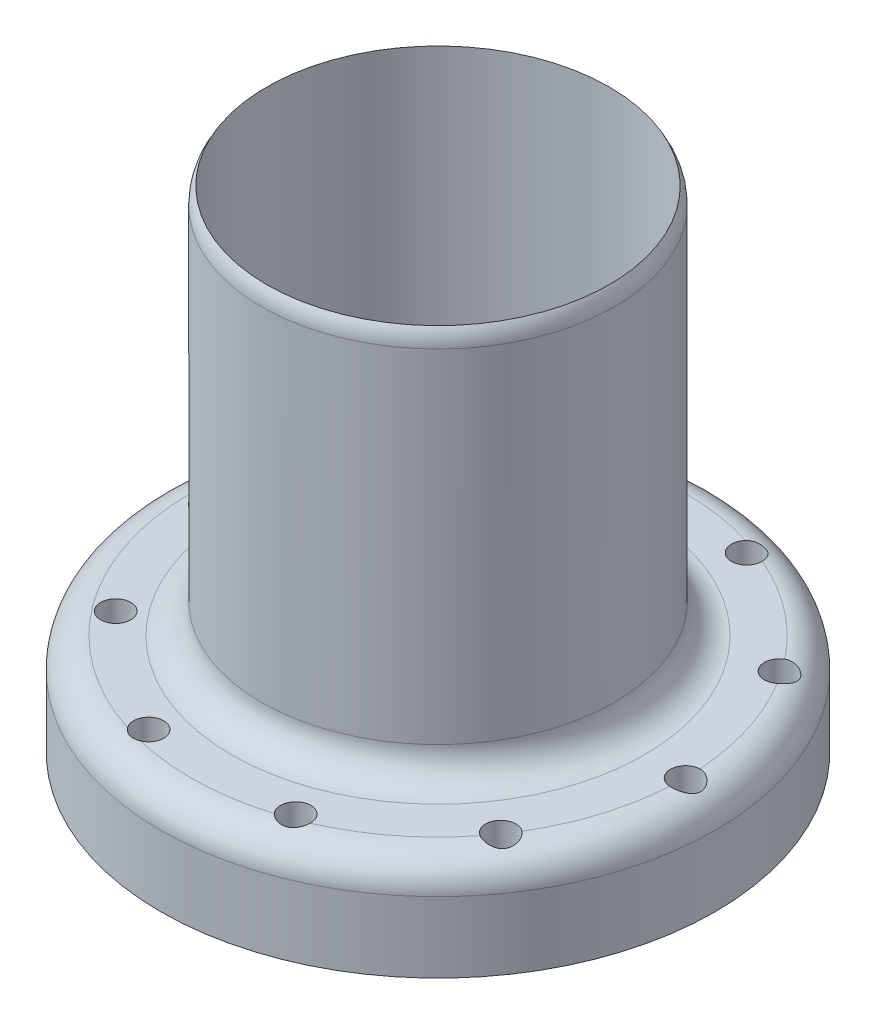
SolidWorks part; units mm, degrees
other "Markup1"
sketch "Sketch6" plane through (45.8333, 74.7453, 45.8333) normal (0.0157, 0.9783, 0.2066) x (0.9999, -0.0155, -0.0025)
ref_plane "Front Plane" through (0, 0, 0) normal (0, 0, 1) x (1, 0, 0)
ref_plane "Top Plane" through (0, 0, 0) normal (0, 1, 0) x (1, 0, 0)
ref_plane "Right Plane" through (0, 0, 0) normal (1, 0, 0) x (0, 0, -1)
sketch "Sketch1" plane through (0, 0, 0) normal (0, 1, 0) x (1, 0, 0)
  circle A0 centre (0, 0) radius 27.5
  circle A1 centre (0, 0) radius 17.5
  dimension "D1" = 35
  dimension "D2" = 10
extrude "Boss-Extrude1" add sketch "Sketch1" along normal blind 50 contours A1
sketch "Sketch2" plane through (0, 50, 0) normal (0, 1, 0) x (1, 0, 0)
  circle A0 centre (0, 0) radius 27.5
  circle A1 centre (0, 0) radius 17.5 construction
  dimension "D1" = 10
extrude "Boss-Extrude2" add sketch "Sketch2" along normal blind 10 from offset 50 offset against normal yes
fillet "Fillet1" radius 3 3 edges at (0, 10, 17.5) (0, 50, 17.5) (0, 10, 27.5)
sketch "Sketch3" plane through (0, 50, 0) normal (0, 1, 0) x (1, 0, 0)
  circle A0 centre (0, 0) radius 17
  dimension "D1" = 34
extrude "Cut-Extrude1" cut sketch "Sketch3" against normal blind 50
sketch "Sketch5" plane through (0, 10, 0) normal (0, 1, 0) x (1, 0, 0)
  line L0 (0, -24.5) -> (0, 24.5) construction
  line L2 (-22.617, -0.0426) -> (22.383, -0.0426) construction
  circle A1 centre (-0.117, -0.0426) radius 22.5 construction
  circle A2 centre (-22.617, -0.0426) radius 1.5
  circle A3 centre (0, 0) radius 24.5 construction
  circle A4 centre (-18.1399, 13.8216) radius 1.5
  circle A5 centre (-6.3688, 22.4063) radius 1.5
  circle A6 centre (8.2003, 22.4326) radius 1.5
  circle A7 centre (20.0024, 13.8904) radius 1.5
  circle A8 centre (24.5295, 0.0426) radius 1.5
  circle A9 centre (20.0524, -13.8216) radius 1.5
  circle A10 centre (8.2812, -22.4063) radius 1.5
  circle A11 centre (-6.2878, -22.4326) radius 1.5
  circle A12 centre (-18.0899, -13.8904) radius 1.5
  point P2 (0, 0)
  point P32 (0.9562, 0)
  dimension "D2" = 3
  dimension "45" = 45
  dimension "D3" = 10
extrude "Cut-Extrude4" cut sketch "Sketch5" against normal blind 10
